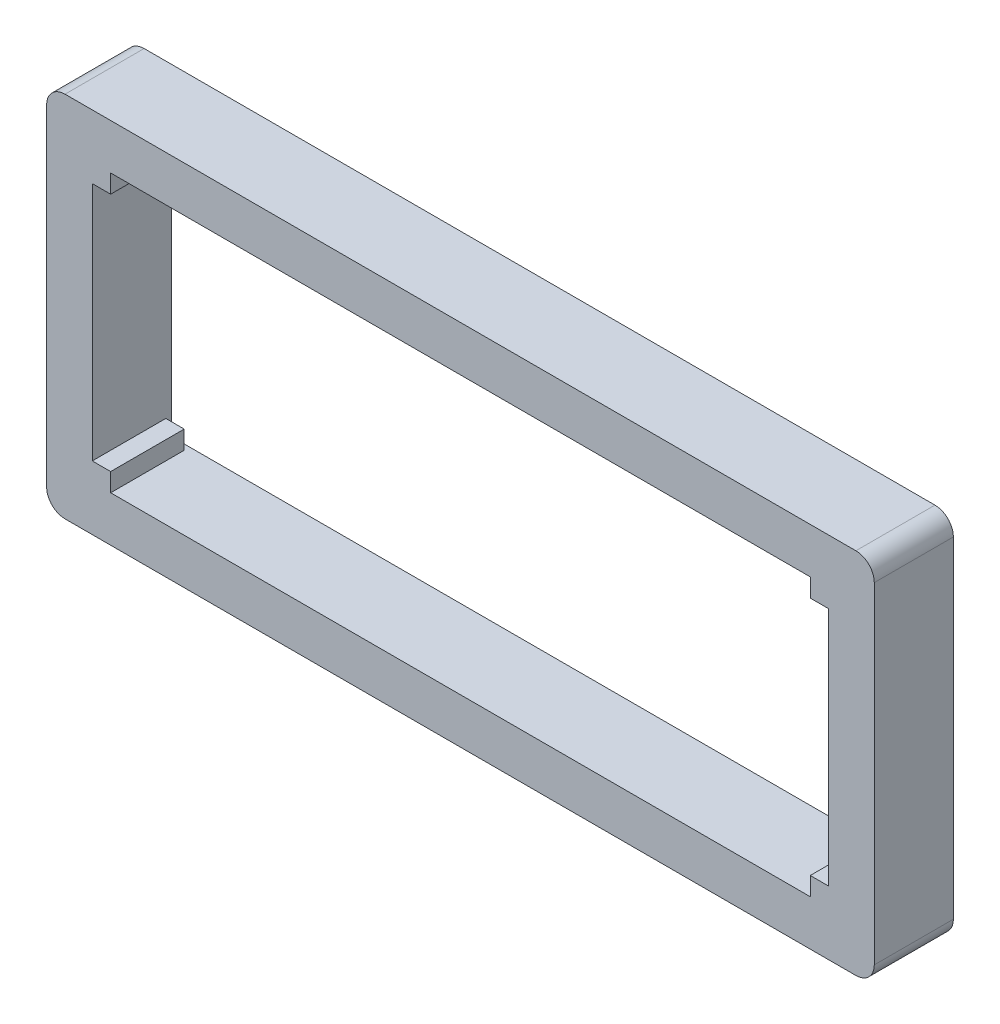
SolidWorks part; units mm, degrees
ref_plane "Front Plane" through (0, 0, 0) normal (0, 0, 1) x (1, 0, 0)
ref_plane "Top Plane" through (0, 0, 0) normal (0, 1, 0) x (1, 0, 0)
ref_plane "Right Plane" through (0, 0, 0) normal (1, 0, 0) x (0, 0, -1)
sketch "Sketch1" plane through (0, 0, 0) normal (0, 0, 1) x (1, 0, 0)
  line L1 (0, 0) -> (200.2, 0)
  line L2 (0, 0) -> (0, 75.3)
  line L3 (0, 75.3) -> (200.2, 75.3)
  line L4 (200.2, 0) -> (200.2, 75.3)
  line L5 (-12.4, 87.65) -> (212.6, 87.65)
  line L6 (-12.4, 87.65) -> (-12.4, -12.35)
  line L7 (-12.4, -12.35) -> (212.6, -12.35)
  line L8 (212.6, 87.65) -> (212.6, -12.35)
  point P9 (0, 37.65)
  point P10 (-12.4, 37.65)
  point P11 (100.1, 75.3)
  point P12 (100.1, 87.65)
  dimension "D1" = 200.2
  dimension "D2" = 75.3
  dimension "D3" = 225
  dimension "D4" = 100
extrude "Boss-Extrude1" add sketch "Sketch1" along normal blind 1.5
sketch "Sketch2" plane through (0, 0, 1.5) normal (0, 0, 1) x (1, 0, 0)
  line L1 (-12.4, 87.65) -> (212.6, 87.65)
  line L2 (-12.4, 87.65) -> (-12.4, -12.35)
  line L3 (-12.4, -12.35) -> (212.6, -12.35)
  line L4 (212.6, 87.65) -> (212.6, -12.35)
  line L5 (0, 75.3) -> (200.2, 75.3)
  line L6 (0, 75.3) -> (0, 0)
  line L7 (0, 0) -> (200.2, 0)
  line L8 (200.2, 75.3) -> (200.2, 0)
  line L9 (0, 75.3) -> (5, 75.3)
  line L10 (0, 75.3) -> (0, 70.3)
  line L11 (0, 70.3) -> (5, 70.3)
  line L12 (5, 75.3) -> (5, 70.3)
  line L13 (0, 0) -> (5, 0)
  line L14 (0, 0) -> (0, 5)
  line L15 (0, 5) -> (5, 5)
  line L16 (5, 0) -> (5, 5)
  line L17 (200.2, 75.3) -> (195.2, 75.3)
  line L18 (200.2, 75.3) -> (200.2, 70.3)
  line L19 (200.2, 70.3) -> (195.2, 70.3)
  line L20 (195.2, 75.3) -> (195.2, 70.3)
  line L21 (200.2, 0) -> (195.2, 0)
  line L22 (200.2, 0) -> (200.2, 5)
  line L23 (200.2, 5) -> (195.2, 5)
  line L24 (195.2, 0) -> (195.2, 5)
  line M25 (-12.4, 87.65) -> (-12.4, -12.35)
  line M26 (-12.4, -12.35) -> (212.6, -12.35)
  line M27 (212.6, -12.35) -> (212.6, 87.65)
  line M28 (212.6, 87.65) -> (-12.4, 87.65)
  line M29 (200.2, 0) -> (0, 0)
  line M30 (0, 0) -> (0, 75.3)
  line M31 (0, 75.3) -> (200.2, 75.3)
  line M32 (200.2, 75.3) -> (200.2, 0)
  dimension "D1" = 5
extrude "Boss-Extrude2" add sketch "Sketch2" along normal blind 20 contours L20 L19 M31 M32 | L24 L23 M29 M32 | L8 L7 L6 L5 M28 M25 M26 M27 M32 M29 M30 M31 | L10 L11 L12 L9 | L13 L16 L15 L14
fillet "Fillet1" radius 5 4 edges at (-12.4, -12.35, 10.75) (212.6, -12.35, 10.75) (212.6, 87.65, 10.75) (-12.4, 87.65, 10.75)
